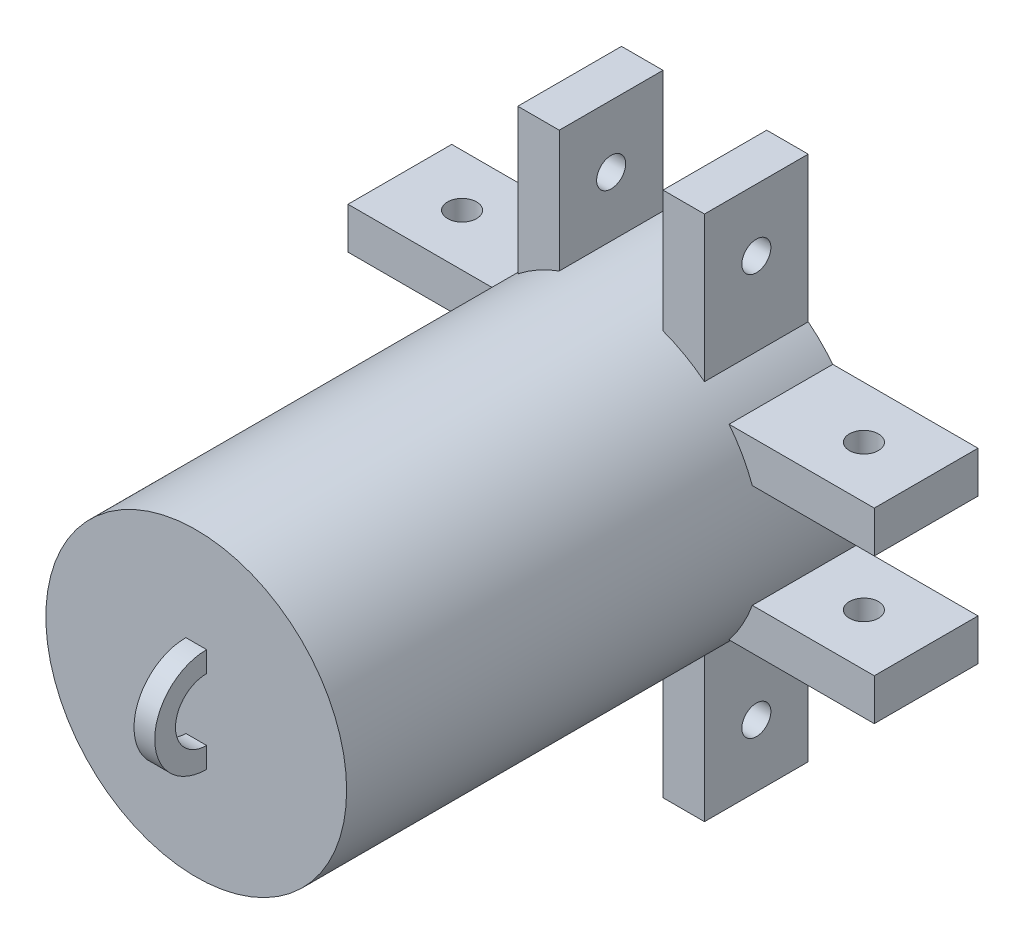
SolidWorks part; units mm, degrees
ref_plane "Front Plane" through (0, 0, 0) normal (0, 0, 1) x (1, 0, 0)
ref_plane "Top Plane" through (0, 0, 0) normal (0, 1, 0) x (1, 0, 0)
ref_plane "Right Plane" through (0, 0, 0) normal (1, 0, 0) x (0, 0, -1)
sketch "Sketch1" plane through (0, 0, 0) normal (0, 0, 1) x (1, 0, 0)
  circle A0 centre (0, 0) radius 18.415
  dimension "D1" = 36.83
extrude "Boss-Extrude1" add sketch "Sketch1" along normal blind 63.5
sketch "Sketch8" plane through (0, 0, 0) normal (0, 0, 1) x (1, 0, 0)
  line L0 (-14.4384, 11.43) -> (-32.2184, 11.43)
  line L1 (-32.2184, 11.43) -> (-32.2184, -11.43)
  line L2 (-32.2184, -11.43) -> (-14.4384, -11.43)
  arc A0 (-14.4384, 11.43) -> (-14.4384, -11.43) centre (0, 0) ccw
  circle A1 centre (0, 0) radius 18.415 construction
  dimension "D1" = 22.86
  dimension "D2" = 17.78
  dimension "D3" = 17.78
extrude "Boss-Extrude4" add sketch "Sketch8" along normal blind 12.7
sketch "Sketch9" plane through (0, -11.43, 0) normal (0, -1, 0) x (1, 0, 0)
  line L1 (-32.2184, 12.7) -> (-32.2184, 0) construction
  circle A0 centre (-24.5984, 6.35) radius 1.778
  point P7 (-32.2184, 6.35)
  dimension "D1" = 3.556
  dimension "D2" = 7.62
extrude "Cut-Extrude2" cut sketch "Sketch9" against normal blind 25.4
sketch "Sketch13" plane through (0, 0, 0) normal (1, 0, 0) x (0, 0, -1)
  line L0 (-63.5, 6.35) -> (-63.5, -6.35)
  line L1 (-63.5, 18.415) -> (-63.5, -18.415) construction
  arc A0 (-63.5, -6.35) -> (-63.5, 6.35) centre (-63.5, 0) cw
  point P5 (-63.5, 7.62)
  dimension "D1" = 6.35
extrude "Boss-Extrude5" add sketch "Sketch13" along normal blind 1.27 and the other way blind 1.27
sketch "Sketch14" plane through (1.27, 0, 0) normal (1, 0, 0) x (0, 0, -1)
  line L0 (-63.5, 3.81) -> (-63.5, -3.81)
  line L1 (-63.5, -6.35) -> (-63.5, 6.35) construction
  arc A0 (-63.5, 3.81) -> (-63.5, -3.81) centre (-63.5, 0) ccw
  arc A1 (-63.5, 6.35) -> (-63.5, -6.35) centre (-63.5, 0) ccw construction
  dimension "D1" = 3.81
extrude "Cut-Extrude3" cut sketch "Sketch14" against normal blind 15.24
sketch "Sketch15" plane through (0, 0, 12.7) normal (0, 0, 1) x (1, 0, 0)
  line L0 (-17.2855, 6.35) -> (-32.2184, 6.35)
  line L1 (-32.2184, 11.43) -> (-32.2184, -11.43) construction
  line L2 (-32.2184, 6.35) -> (-32.2184, -6.35)
  line L3 (-32.2184, -6.35) -> (-17.2855, -6.35)
  arc A0 (-17.2855, 6.35) -> (-17.2855, -6.35) centre (0, 0) ccw
  arc A1 (-14.4384, 11.43) -> (-14.4384, -11.43) centre (0, 0) ccw construction
  point P7 (-32.2184, 0)
  dimension "D1" = 12.7
extrude "Cut-Extrude4" cut sketch "Sketch15" against normal blind 12.7
pattern_circular "CirPattern1" count 4 over 360 about axis through (0, 0, 0) along (0, 0, 1) of "Boss-Extrude4", "Cut-Extrude2", "Cut-Extrude4"
